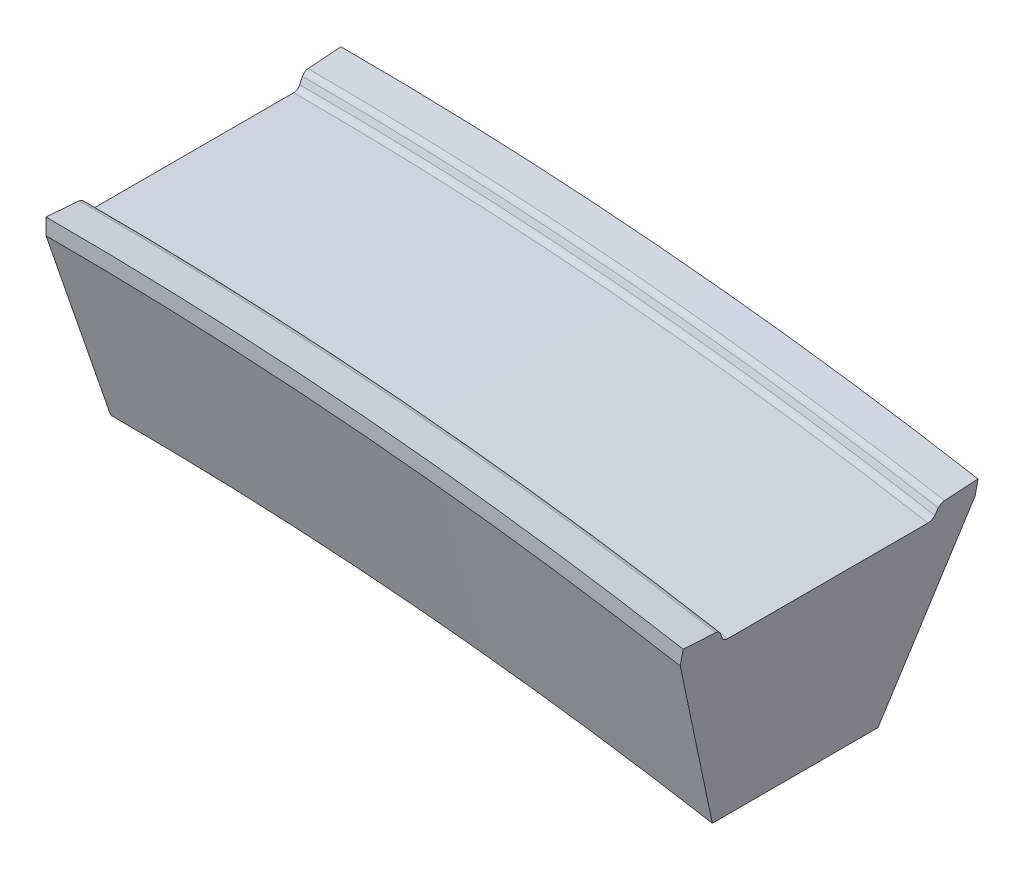
SolidWorks part; units mm, degrees
ref_plane "Alzado" through (0, 0, 0) normal (0, 0, 1) x (1, 0, 0)
ref_plane "Planta" through (0, 0, 0) normal (0, 1, 0) x (1, 0, 0)
ref_plane "Vista lateral" through (0, 0, 0) normal (1, 0, 0) x (0, 0, -1)
sketch "Croquis1" plane through (0, 0, 0) normal (1, 0, 0) x (0, 0, -1)
  line L0 (-417.6317, 0) -> (417.6317, 0) construction
  line L1 (0, -286.5) -> (0, 286.5) construction
  line L2 (7.8, 272.5) -> (-7.4767, 272.5) construction
  line L3 (-7.9327, 272.7948) -> (-8.1282, 273.2294)
  line L4 (-8.5458, 273.5228) -> (-12.6828, 273.841)
  line L5 (-14.9762, 276.0609) -> (-16, 285.3909)
  line L6 (-16, 285.3909) -> (-14.0119, 285.6091) construction
  line L7 (-15.006, 285.5) -> (-14.3695, 279.7) construction
  line L8 (-14.8969, 284.506) -> (-14.3695, 279.7)
  line L9 (15.006, 285.5) -> (14.3695, 279.7) construction
  line L14 (16, 285.3909) -> (14.0119, 285.6091) construction
  line L15 (14.8969, 284.506) -> (14.3695, 279.7)
  line L16 (14.9762, 276.0609) -> (16, 285.3909)
  line L17 (8.5458, 273.5228) -> (12.6828, 273.841)
  line L18 (7.9327, 272.7948) -> (8.1282, 273.2294)
  line L19 (-14.75, 274) -> (-12.4911, 276.3336) construction
  line L20 (7.4767, 272.5) -> (-7.4767, 272.5)
  arc A0 (-14.8969, 284.506) -> (-16, 285.3909) centre (-15.006, 285.5) ccw
  arc A1 (-14.3695, 279.7) -> (-9.3, 275) centre (-14.7434, 274.2127) cw
  arc A2 (-9.3, 275) -> (0, 274.3) centre (0.7427, 346.2962) ccw
  arc A6 (-12.6828, 273.841) -> (-14.9762, 276.0609) centre (-12.4911, 276.3336) cw
  arc A7 (-8.1282, 273.2294) -> (-8.5458, 273.5228) centre (-8.5842, 273.0242) ccw
  arc A8 (-7.9327, 272.7948) -> (-7.4767, 272.5) centre (-7.4767, 273) ccw
  arc A9 (7.9327, 272.7948) -> (7.4767, 272.5) centre (7.4767, 273) cw
  arc A10 (8.1282, 273.2294) -> (8.5458, 273.5228) centre (8.5842, 273.0242) cw
  arc A11 (12.6828, 273.841) -> (14.9762, 276.0609) centre (12.4911, 276.3336) ccw
  arc A12 (9.3, 275) -> (0, 274.3) centre (-0.7427, 346.2962) cw
  arc A13 (14.3695, 279.7) -> (9.3, 275) centre (14.7434, 274.2127) ccw
  arc A14 (14.8969, 284.506) -> (16, 285.3909) centre (15.006, 285.5) cw
  point P4 (0, 0)
  point P8 (0, 0)
  point P22 (-15.006, 286.5)
  point P33 (-14.75, 274)
  point P36 (-8.25, 273.5)
  point P39 (-7.8, 272.5)
  point P54 (8.25, 273.5)
  point P55 (14.75, 274)
  point P56 (15.006, 286.5)
  point P57 (-14.2299, 274.5373)
  dimension "D7" = 2
  dimension "D14" = 72
  dimension "D15" = 5.5
  dimension "D16" = 2.5
  dimension "D17" = 0.5
  dimension "D18" = 0.5
  dimension "D2" = 548
  dimension "D3" = 15.6
  dimension "D4" = 29.5
  dimension "D5" = 1
  dimension "D6" = 6.5
  dimension "D8" = 14
  dimension "D9" = 8.2
  dimension "D10" = 0.7
  dimension "D11" = 6.8
  dimension "D12" = 11.5
  dimension "D13" = 6.7
  dimension "D19" = 545
revolve "Revolución2" add sketch "Croquis1" angle 360 about L0
sketch "Croquis2" plane through (0, 0, 0) normal (0, 1, 0) x (1, 0, 0)
  circle A0 centre (0, 0) radius 2.1
  dimension "D1" = 4.2
extrude "Cortar-Extruir1" cut sketch "Croquis2" against normal through all
pattern_circular "MatrizC1" count 36 over 360 about axis through (0, 0, 0) along (0, 0, 1) of "Cortar-Extruir1"
sketch "Croquis3" plane through (0, 0, 0) normal (0, 0, 1) x (1, 0, 0)
  line L0 (0, 0) -> (-236.4938, 138.9646)
  line L1 (0, 0) -> (-211.4697, 174.7028)
  line L2 (0, 0) -> (-224.6934, 157.332)
  arc A2 (-211.4697, 174.7028) -> (-236.4938, 138.9646) centre (0, 0) ccw construction
  arc A3 (-211.4697, 174.7028) -> (-236.4938, 138.9646) centre (0, 0) ccw
  point P7 (-224.6934, 157.332)
  point P9 (-224.6934, 157.332)
ref_plane "Plano1" through (-224.6934, 157.332, 0) normal (-0.8192, 0.5736, 0) x (0, 0, -1)
sketch "Croquis4" plane through (-224.6934, 157.332, 0) normal (-0.8192, 0.5736, 0) x (0, 0, -1)
  circle A0 centre (0, 0) radius 4.2
  dimension "D1" = 8.4
extrude "Cortar-Extruir5" cut sketch "Croquis4" against normal up to next and the other way up to next
sketch "Croquis5" plane through (0, 0, 0) normal (1, 0, 0) x (0, 0, -1)
  line L0 (-11, 272.5) -> (11, 272.5) construction
  line L1 (-7.4767, 272.5) -> (7.4767, 272.5)
  line L2 (7.9327, 272.7948) -> (8.1282, 273.2294) construction
  line L3 (8.5458, 273.5228) -> (12.6828, 273.841) construction
  line L4 (7.4767, 272.5) -> (-7.4767, 272.5) construction
  line L5 (-7.9327, 272.7948) -> (-8.1282, 273.2294) construction
  line L6 (-8.5458, 273.5228) -> (-12.6828, 273.841) construction
  line L7 (7.9327, 272.7948) -> (8.1282, 273.2294)
  line L8 (8.5458, 273.5228) -> (11, 273.7115)
  line L9 (7.4767, 272.5) -> (-7.4767, 272.5)
  line L10 (-7.9327, 272.7948) -> (-8.1282, 273.2294)
  line L11 (-8.5458, 273.5228) -> (-11, 273.7115)
  line L12 (-11, 272.5) -> (-6.1794, 258.5)
  line L13 (-6.1794, 258.5) -> (6.1794, 258.5)
  line L14 (6.1794, 258.5) -> (11, 272.5)
  line L15 (0, -286.5) -> (0, 286.5) construction
  line L16 (-11, 272.5) -> (-11, 273.7115)
  line L17 (11, 272.5) -> (11, 273.7115)
  line L18 (0, -286.5) -> (0, 286.5)
  line L19 (-417.6317, 0) -> (417.6317, 0) construction
  line L20 (-417.6317, 0) -> (417.6317, 0)
  arc A0 (7.4767, 272.5) -> (7.9327, 272.7948) centre (7.4767, 273) ccw construction
  arc A1 (8.5458, 273.5228) -> (8.1282, 273.2294) centre (8.5842, 273.0242) ccw construction
  arc A2 (-7.9327, 272.7948) -> (-7.4767, 272.5) centre (-7.4767, 273) ccw construction
  arc A3 (-8.1282, 273.2294) -> (-8.5458, 273.5228) centre (-8.5842, 273.0242) ccw construction
  arc A4 (7.4767, 272.5) -> (7.9327, 272.7948) centre (7.4767, 273) ccw
  arc A5 (8.5458, 273.5228) -> (8.1282, 273.2294) centre (8.5842, 273.0242) ccw
  arc A6 (-7.9327, 272.7948) -> (-7.4767, 272.5) centre (-7.4767, 273) ccw
  arc A7 (-8.1282, 273.2294) -> (-8.5458, 273.5228) centre (-8.5842, 273.0242) ccw
  point P3 (0, 272.5)
  point P7 (0, 272.5)
  point P14 (0, 258.5)
  dimension "D1" = 22
  dimension "D2" = 14
  dimension "D3" = 38
revolve "Revolución3" add sketch "Croquis5" angle 10 about L20
delete or keep bodies "Sólido-Eliminar/Conservar 1" type delete bodies bodies 106
